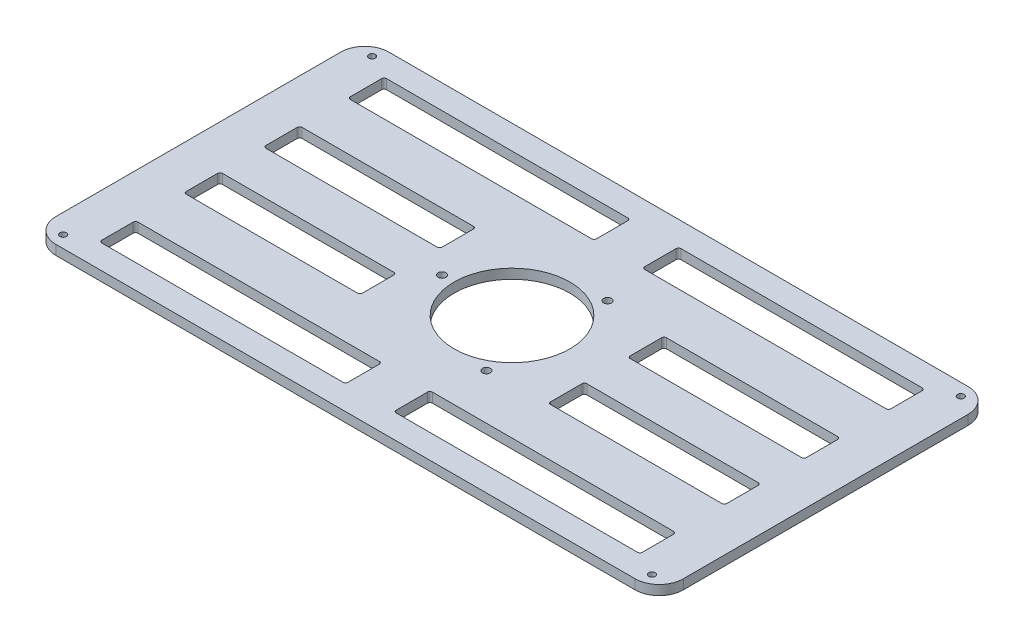
SolidWorks part; units mm, degrees
ref_plane "前视基准面" through (0, 0, 0) normal (0, 0, 1) x (1, 0, 0)
ref_plane "上视基准面" through (0, 0, 0) normal (0, 1, 0) x (1, 0, 0)
ref_plane "右视基准面" through (0, 0, 0) normal (1, 0, 0) x (0, 0, -1)
other "Configuration Table"
sketch "草图1" plane through (0, 0, 0) normal (0, 1, 0) x (1, 0, 0)
  line L0 (-215.7348, 0) -> (258.2915, 0) construction
  line L1 (-130, -69) -> (130, -69)
  line L2 (-130, -69) -> (-130, 69)
  line L3 (-130, 69) -> (130, 69)
  line L4 (130, -69) -> (130, 69)
  line L5 (-130, -69) -> (130, 69) construction
  line L6 (-130, 69) -> (130, -69) construction
  line L7 (0, 138.0224) -> (0, -163.614) construction
  circle A0 centre (-122, 64) radius 1.35
  circle A1 centre (122, 64) radius 1.35
  circle A2 centre (122, -64) radius 1.35
  circle A3 centre (-122, -64) radius 1.35
  point P0 (0, 0)
  dimension "D3" = 2.7
  dimension "D4" = 244
  dimension "D5" = 128
  dimension "D1" = 260
  dimension "D2" = 138
extrude "凸台-拉伸1" add sketch "草图1" along normal blind 4
sketch "草图3" plane through (0, 4, 0) normal (0, 1, 0) x (1, 0, 0)
  circle A0 centre (0, 0) radius 24
  circle A1 centre (-29, 0) radius 1.65
  circle A2 centre (14.5, 25.1147) radius 1.65
  circle A3 centre (14.5, -25.1147) radius 1.65
  point P11 (0, 0)
  dimension "D1" = 48
  dimension "D3" = 3.3
  dimension "D4" = 29
  dimension "D2" = 3
extrude "切除-拉伸1" cut sketch "草图3" against normal up to surface (4 mm away) up to face at (122, 0, 65.35)
sketch "草图4" plane through (0, 4, 0) normal (0, 1, 0) x (1, 0, 0)
  line L0 (-154.3254, 0) -> (160.361, 0) construction
  line L1 (-111, 59) -> (-11, 59)
  line L2 (-112, 58) -> (-112, 45)
  line L3 (-111, 44) -> (-11, 44)
  line L4 (-10, 58) -> (-10, 45)
  line L5 (-111, 24) -> (-40, 24)
  line L6 (-112, 23) -> (-112, 10)
  line L7 (-111, 9) -> (-40, 9)
  line L8 (-39, 23) -> (-39, 10)
  line L9 (130, 69) -> (-130, 69) construction
  line L11 (0, 0) -> (0, 202.1374) construction
  line L39 (111, 9) -> (40, 9)
  line L40 (39, 23) -> (39, 10)
  line L41 (111, 24) -> (40, 24)
  line L42 (112, 23) -> (112, 10)
  line L55 (111, 44) -> (11, 44)
  line L56 (10, 58) -> (10, 45)
  line L57 (111, 59) -> (11, 59)
  line L58 (112, 58) -> (112, 45)
  line L59 (111, -9) -> (40, -9)
  line L60 (112, -23) -> (112, -10)
  line L61 (111, -24) -> (40, -24)
  line L62 (39, -23) -> (39, -10)
  line L71 (-111, -9) -> (-40, -9)
  line L72 (-39, -23) -> (-39, -10)
  line L73 (-111, -24) -> (-40, -24)
  line L74 (-112, -23) -> (-112, -10)
  line L99 (111, -44) -> (11, -44)
  line L100 (112, -58) -> (112, -45)
  line L101 (111, -59) -> (11, -59)
  line L102 (10, -58) -> (10, -45)
  line L103 (-111, -44) -> (-11, -44)
  line L104 (-10, -58) -> (-10, -45)
  line L105 (-111, -59) -> (-11, -59)
  line L106 (-112, -58) -> (-112, -45)
  circle A0 centre (-122, 64) radius 1.35 construction
  arc A1 (-11, 44) -> (-10, 45) centre (-11, 45) ccw
  arc A2 (-11, 59) -> (-10, 58) centre (-11, 58) cw
  arc A3 (-112, 45) -> (-111, 44) centre (-111, 45) ccw
  arc A4 (-111, 59) -> (-112, 58) centre (-111, 58) ccw
  circle A17 centre (-29, 0) radius 1.65 construction
  arc A18 (-40, 24) -> (-39, 23) centre (-40, 23) cw
  arc A19 (-40, 9) -> (-39, 10) centre (-40, 10) ccw
  arc A20 (-112, 10) -> (-111, 9) centre (-111, 10) ccw
  arc A21 (-111, 24) -> (-112, 23) centre (-111, 23) ccw
  arc A38 (40, 9) -> (39, 10) centre (40, 10) cw
  arc A39 (40, 24) -> (39, 23) centre (40, 23) ccw
  arc A40 (112, 10) -> (111, 9) centre (111, 10) cw
  arc A41 (111, 24) -> (112, 23) centre (111, 23) cw
  arc A54 (11, 44) -> (10, 45) centre (11, 45) cw
  arc A55 (11, 59) -> (10, 58) centre (11, 58) ccw
  arc A56 (112, 45) -> (111, 44) centre (111, 45) cw
  arc A57 (111, 59) -> (112, 58) centre (111, 58) cw
  arc A58 (112, -10) -> (111, -9) centre (111, -10) ccw
  arc A59 (111, -24) -> (112, -23) centre (111, -23) ccw
  arc A60 (40, -24) -> (39, -23) centre (40, -23) cw
  arc A61 (40, -9) -> (39, -10) centre (40, -10) ccw
  arc A70 (-40, -9) -> (-39, -10) centre (-40, -10) cw
  arc A71 (-40, -24) -> (-39, -23) centre (-40, -23) ccw
  arc A72 (-112, -10) -> (-111, -9) centre (-111, -10) cw
  arc A73 (-111, -24) -> (-112, -23) centre (-111, -23) cw
  arc A98 (112, -45) -> (111, -44) centre (111, -45) ccw
  arc A99 (111, -59) -> (112, -58) centre (111, -58) ccw
  arc A100 (11, -59) -> (10, -58) centre (11, -58) cw
  arc A101 (11, -44) -> (10, -45) centre (11, -45) ccw
  arc A102 (-11, -44) -> (-10, -45) centre (-11, -45) cw
  arc A103 (-11, -59) -> (-10, -58) centre (-11, -58) ccw
  arc A104 (-112, -45) -> (-111, -44) centre (-111, -45) cw
  arc A105 (-111, -59) -> (-112, -58) centre (-111, -58) cw
  point P23 (-112, 44)
  point P26 (-112, 59)
  point P71 (-112, 9)
  point P74 (-112, 24)
  dimension "D4" = 1
  dimension "D11" = 1
  dimension "D1" = 10
  dimension "D2" = 15
  dimension "D3" = 10
  dimension "D7" = 10
  dimension "D8" = 10
  dimension "D9" = 15
  dimension "D5" = 20
extrude "切除-拉伸3" cut sketch "草图4" against normal up to surface (4 mm away) up to face at (14.5, 0, 23.4647)
fillet "圆角1" radius 10 4 edges at (130, 2, -69) (130, 2, 69) (-130, 2, 69) (-130, 2, -69)
